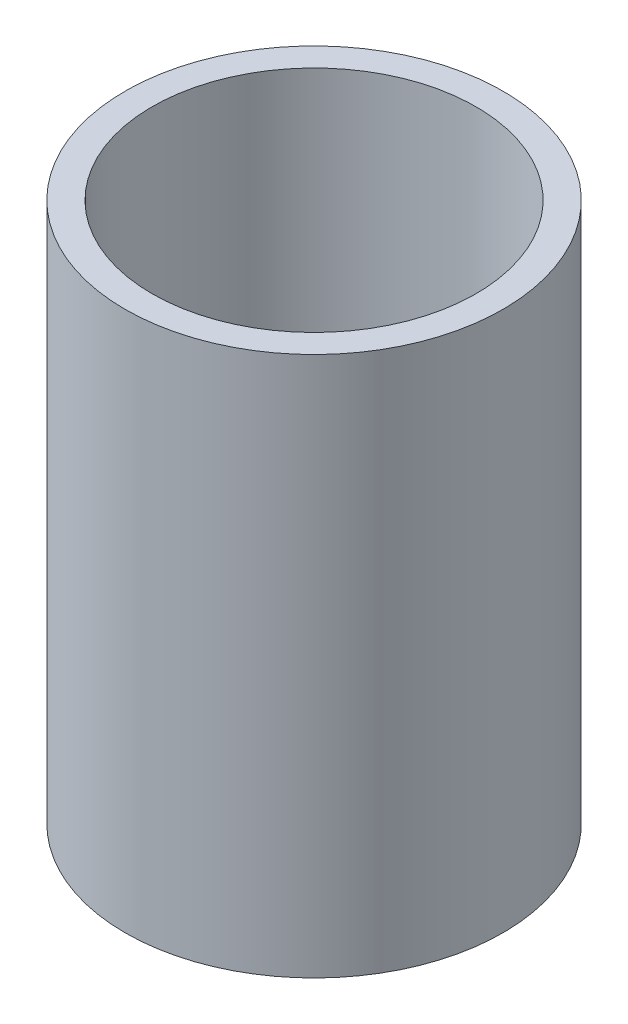
SolidWorks part; units mm, degrees
ref_plane "Plan de face" through (0, 0, 0) normal (0, 0, 1) x (1, 0, 0)
ref_plane "Plan de dessus" through (0, 0, 0) normal (0, 1, 0) x (1, 0, 0)
ref_plane "Plan de droite" through (0, 0, 0) normal (1, 0, 0) x (0, 0, -1)
sketch "Esquisse1" plane through (0, 0, 0) normal (0, 1, 0) x (1, 0, 0)
  circle A0 centre (0, 0) radius 17.5
  dimension "D1" = 35
extrude "Boss.-Extru.1" add sketch "Esquisse1" along normal blind 50
sketch "Esquisse2" plane through (0, 50, 0) normal (0, 1, 0) x (1, 0, 0)
  circle A0 centre (0, 0) radius 15
  dimension "D1" = 30
extrude "Enlèv. mat.-Extru.1" cut sketch "Esquisse2" against normal blind 45
